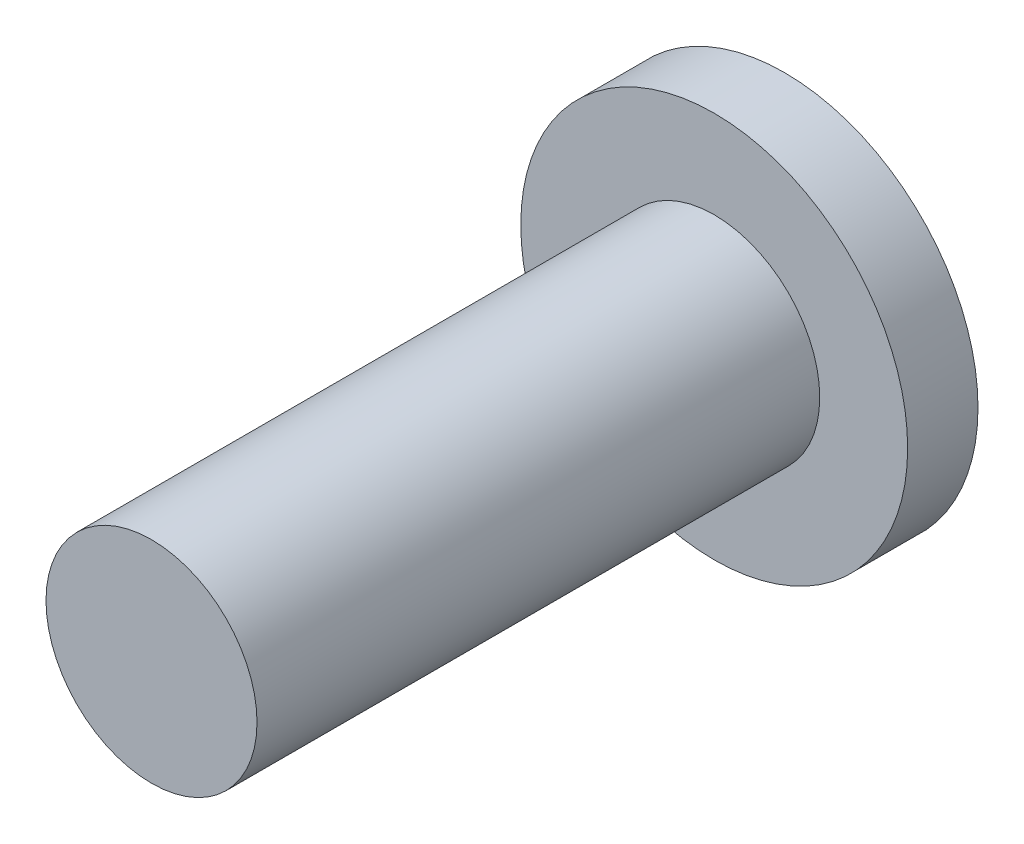
SolidWorks part; units mm, degrees
ref_plane "正面" through (0, 0, 0) normal (0, 0, 1) x (1, 0, 0)
ref_plane "平面" through (0, 0, 0) normal (0, 1, 0) x (1, 0, 0)
ref_plane "右側面" through (0, 0, 0) normal (1, 0, 0) x (0, 0, -1)
sketch "ｽｹｯﾁ1" plane through (0, 0, 0) normal (0, 0, 1) x (1, 0, 0)
  circle A0 centre (0, 0) radius 2.75
  dimension "D1" = 5.5
extrude "ﾎﾞｽ - 押し出し1" add sketch "ｽｹｯﾁ1" along normal blind 1
sketch "ｽｹｯﾁ2" plane through (0, 0, 1) normal (0, 0, 1) x (1, 0, 0)
  circle A0 centre (0, 0) radius 1.5
  dimension "D1" = 3
extrude "ﾎﾞｽ - 押し出し2" add sketch "ｽｹｯﾁ2" along normal blind 8
cosmetic thread "ねじ山1" parameters "D2"=2.439
sketch "ｽｹｯﾁ3" plane through (0, 0, 0) normal (0, 0, -1) x (-1, 0, 0)
  line L1 (-1.5, -0.5) -> (1.5, -0.5)
  line L2 (-1.5, -0.5) -> (-1.5, 0.5)
  line L3 (-1.5, 0.5) -> (1.5, 0.5)
  line L4 (1.5, -0.5) -> (1.5, 0.5)
  line L5 (-1.5, -0.5) -> (1.5, 0.5) construction
  line L6 (-1.5, 0.5) -> (1.5, -0.5) construction
  line L7 (-0.5, -1.5) -> (0.5, -1.5)
  line L8 (-0.5, -1.5) -> (-0.5, 1.5)
  line L9 (-0.5, 1.5) -> (0.5, 1.5)
  line L10 (0.5, -1.5) -> (0.5, 1.5)
  line L11 (-0.5, -1.5) -> (0.5, 1.5) construction
  line L12 (-0.5, 1.5) -> (0.5, -1.5) construction
  point P0 (0, 0)
  point P5 (0, 0)
  dimension "D1" = 1
  dimension "D2" = 1
  dimension "D3" = 3
  dimension "D4" = 3
extrude "ｶｯﾄ - 押し出し1" cut sketch "ｽｹｯﾁ3" against normal blind 0.5 contours L3 L10 L9 L8 | L1 L10 L3 L8 | L10 L1 L4 L3 | L1 L8 L3 L2 | L7 L10 L1 L8
